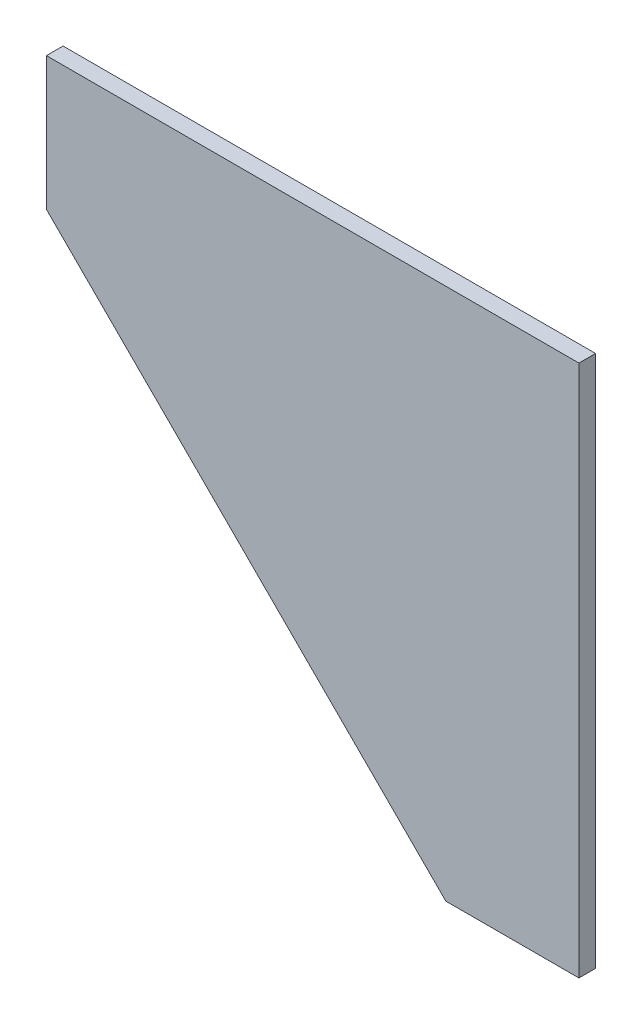
SolidWorks part; units mm, degrees
material "Plain Carbon Steel"
ref_plane "Front Plane" through (0, 0, 0) normal (0, 0, 1) x (1, 0, 0)
ref_plane "Top Plane" through (0, 0, 0) normal (0, 1, 0) x (1, 0, 0)
ref_plane "Right Plane" through (0, 0, 0) normal (1, 0, 0) x (0, 0, -1)
sketch "Sketch1" plane through (0, 0, 0) normal (0, 0, 1) x (1, 0, 0)
  line L0 (0, 0) -> (0, 203.2)
  line L1 (0, 203.2) -> (-203.2, 203.2)
  line L2 (-203.2, 203.2) -> (-203.2, 152.4)
  line L3 (-203.2, 152.4) -> (-50.8, 0)
  line L4 (-50.8, 0) -> (0, 0)
  dimension "D1" = 50.8
  dimension "D2" = 203.2
extrude "Boss-Extrude1" add sketch "Sketch1" along normal blind 6.35
